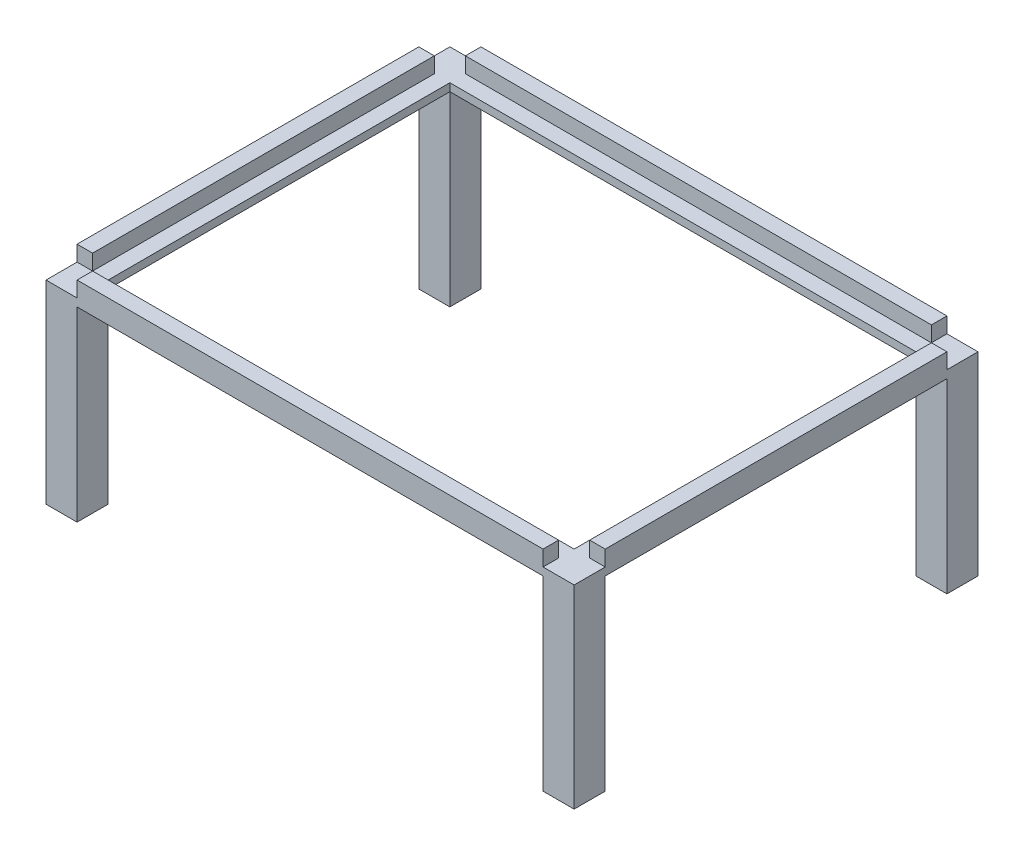
SolidWorks part; units mm, degrees
ref_plane "Front Plane" through (0, 0, 0) normal (0, 0, 1) x (1, 0, 0)
ref_plane "Top Plane" through (0, 0, 0) normal (0, 1, 0) x (1, 0, 0)
ref_plane "Right Plane" through (0, 0, 0) normal (1, 0, 0) x (0, 0, -1)
sketch "Sketch1" plane through (0, 0, 0) normal (0, 1, 0) x (1, 0, 0)
  line L1 (190.5, 139.7) -> (-190.5, 139.7)
  line L2 (190.5, 139.7) -> (190.5, -139.7)
  line L3 (190.5, -139.7) -> (-190.5, -139.7)
  line L4 (-190.5, 139.7) -> (-190.5, -139.7)
  line L5 (190.5, 139.7) -> (-190.5, -139.7) construction
  line L6 (190.5, -139.7) -> (-190.5, 139.7) construction
  line L7 (215.9, 165.1) -> (-215.9, 165.1)
  line L8 (215.9, 165.1) -> (215.9, -165.1)
  line L9 (215.9, -165.1) -> (-215.9, -165.1)
  line L10 (-215.9, 165.1) -> (-215.9, -165.1)
  line L11 (215.9, 165.1) -> (-215.9, -165.1) construction
  line L12 (215.9, -165.1) -> (-215.9, 165.1) construction
  point P0 (0, 0)
  point P6 (0, 0)
  dimension "D1" = 25.4
  dimension "D2" = 25.4
  dimension "D3" = 279.4
  dimension "D4" = 381
extrude "Boss-Extrude1" add sketch "Sketch1" along normal blind 6.35
sketch "Sketch2" plane through (0, 0, 0) normal (0, 1, 0) x (1, 0, 0)
  line L0 (-215.9, -165.1) -> (215.9, -165.1) construction
  line L1 (-190.5, -139.7) -> (-215.9, -139.7)
  line L2 (-190.5, -139.7) -> (-190.5, -165.1)
  line L3 (-190.5, -165.1) -> (-215.9, -165.1)
  line L4 (-215.9, -139.7) -> (-215.9, -165.1)
  line L6 (-190.5, 139.7) -> (-215.9, 139.7)
  line L7 (-190.5, 139.7) -> (-190.5, 165.1)
  line L8 (-190.5, 165.1) -> (-215.9, 165.1)
  line L9 (-215.9, 139.7) -> (-215.9, 165.1)
  line L10 (190.5, 139.7) -> (215.9, 139.7)
  line L11 (190.5, 139.7) -> (190.5, 165.1)
  line L12 (190.5, 165.1) -> (215.9, 165.1)
  line L13 (215.9, 139.7) -> (215.9, 165.1)
  line L14 (190.5, -139.7) -> (215.9, -139.7)
  line L15 (190.5, -139.7) -> (190.5, -165.1)
  line L16 (190.5, -165.1) -> (215.9, -165.1)
  line L17 (215.9, -139.7) -> (215.9, -165.1)
extrude "Boss-Extrude2" add sketch "Sketch2" against normal blind 152.4
sketch "Sketch3" plane through (0, 6.35, 0) normal (0, 1, 0) x (1, 0, 0)
  line L0 (-215.9, 165.1) -> (-215.9, -165.1) construction
  line L1 (-203.2, -139.7) -> (-215.9, -139.7)
  line L2 (-203.2, -139.7) -> (-203.2, 139.7)
  line L3 (-203.2, 139.7) -> (-215.9, 139.7)
  line L4 (-215.9, -139.7) -> (-215.9, 139.7)
  line L5 (-190.5, -139.7) -> (190.5, -139.7) construction
  line L6 (190.5, 139.7) -> (-190.5, 139.7) construction
  line L7 (190.5, -139.7) -> (190.5, 139.7) construction
  line L8 (-190.5, 165.1) -> (190.5, 165.1)
  line L9 (-190.5, 165.1) -> (-190.5, 152.4)
  line L10 (-190.5, 152.4) -> (190.5, 152.4)
  line L11 (190.5, 165.1) -> (190.5, 152.4)
  line L12 (215.9, 139.7) -> (203.2, 139.7)
  line L13 (215.9, 139.7) -> (215.9, -139.7)
  line L14 (215.9, -139.7) -> (203.2, -139.7)
  line L15 (203.2, 139.7) -> (203.2, -139.7)
  line L16 (190.5, -165.1) -> (-190.5, -165.1)
  line L17 (190.5, -165.1) -> (190.5, -152.4)
  line L18 (190.5, -152.4) -> (-190.5, -152.4)
  line L19 (-190.5, -165.1) -> (-190.5, -152.4)
  line L20 (-190.5, 139.7) -> (-190.5, -139.7) construction
  dimension "D1" = 12.7
  dimension "D2" = 12.7
  dimension "D3" = 12.7
  dimension "D4" = 12.7
extrude "Boss-Extrude3" add sketch "Sketch3" along normal blind 12.7
